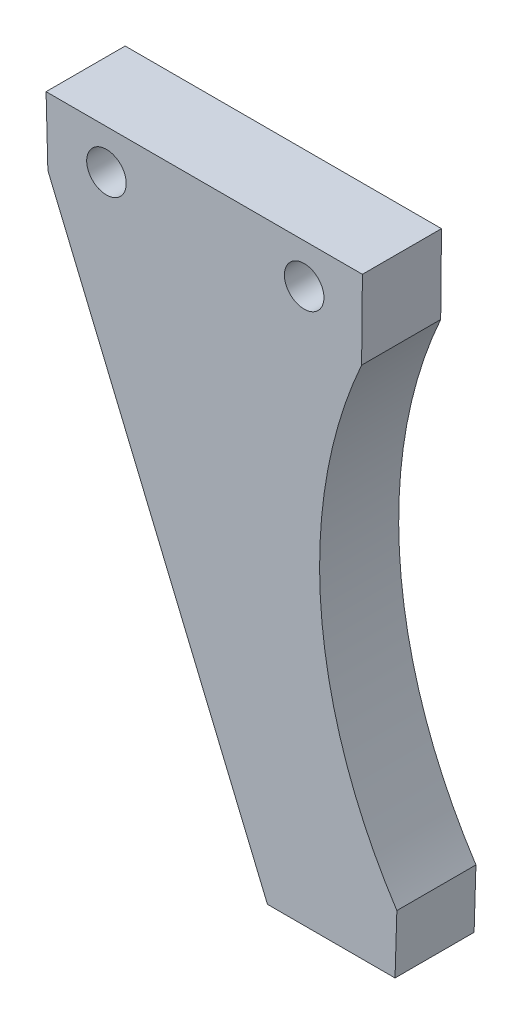
SolidWorks part; units mm, degrees
ref_plane "前视基准面" through (0, 0, 0) normal (0, 0, 1) x (1, 0, 0)
ref_plane "上视基准面" through (0, 0, 0) normal (0, 1, 0) x (1, 0, 0)
ref_plane "右视基准面" through (0, 0, 0) normal (1, 0, 0) x (0, 0, -1)
sketch "草图1" plane through (0, 0, 0) normal (0, 0, 1) x (1, 0, 0)
  line L0 (-60.096, 27.6946) -> (19.904, 27.6946)
  line L1 (19.904, 27.6946) -> (19.7063, 7.6946)
  line L2 (-60.096, 27.6946) -> (-59.6435, 10.6729)
  line L3 (-59.6435, 10.6729) -> (-4.1094, -122.3054)
  line L4 (-4.1094, -122.3054) -> (28.1569, -122.3054)
  line L5 (28.1569, -122.3054) -> (28.6179, -107.3054)
  arc A0 (19.7063, 7.6946) -> (28.6179, -107.3054) centre (129.0801, -41.6751) ccw
  circle A1 centre (-44.8249, 17.6946) radius 5
  circle A2 centre (5.1751, 17.6946) radius 5
  dimension "D1" = 150
  dimension "D2" = 15
  dimension "D5" = 50
  dimension "D6" = 15
  dimension "D7" = 10
  dimension "D8" = 10
  dimension "D3" = 20
  dimension "D4" = 80
extrude "凸台-拉伸2" add sketch "草图1" along normal blind 20
